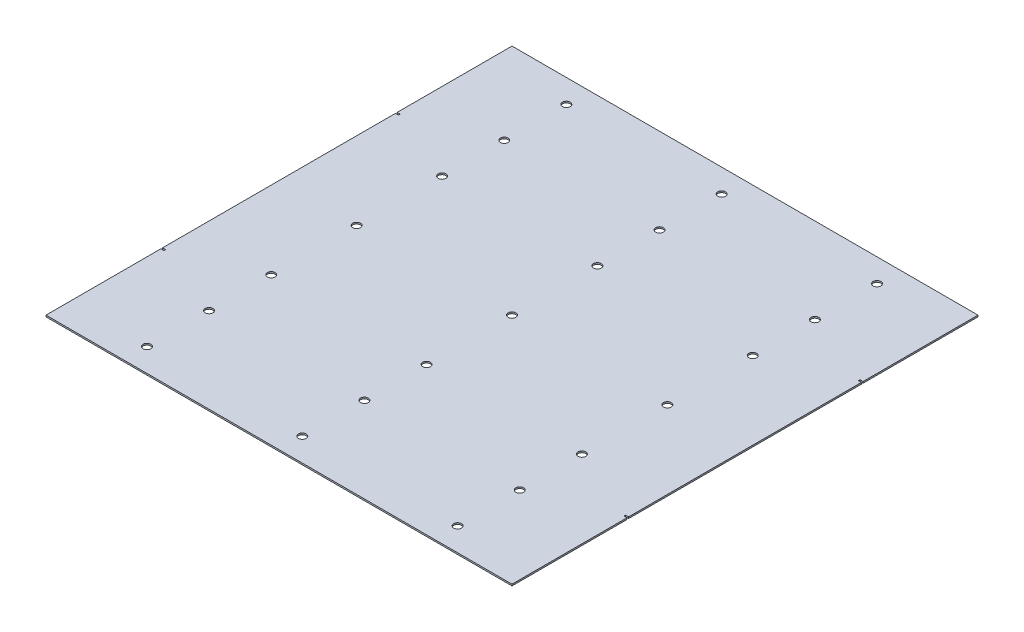
SolidWorks part; units mm, degrees
ref_plane "Front Plane" through (0, 0, 0) normal (0, 0, 1) x (1, 0, 0)
ref_plane "Top Plane" through (0, 0, 0) normal (0, 1, 0) x (1, 0, 0)
ref_plane "Right Plane" through (0, 0, 0) normal (1, 0, 0) x (0, 0, -1)
sketch "Sketch1" plane through (0, 0, 0) normal (0, 1, 0) x (1, 0, 0)
  line L0 (0, 0) -> (0, 74)
  line L5 (0, 74) -> (2, 74)
  line L6 (2, 74) -> (2, 75)
  line L11 (2, 75) -> (0, 75)
  line L12 (0, 75) -> (0, 225)
  line L51 (0, 225) -> (2, 225)
  line L53 (2, 225) -> (2, 226)
  line L54 (2, 226) -> (0, 226)
  line L55 (0, 226) -> (0, 300)
  line L56 (0, 300) -> (300, 300)
  line L57 (300, 300) -> (300, 226)
  line L58 (300, 226) -> (298, 226)
  line L59 (298, 226) -> (298, 225)
  line L60 (298, 225) -> (300, 225)
  line L61 (300, 225) -> (300, 75)
  line L62 (300, 75) -> (298, 75)
  line L63 (298, 75) -> (298, 74)
  line L64 (298, 74) -> (300, 74)
  line L65 (300, 74) -> (300, 0)
  line L66 (300, 0) -> (0, 0)
  line L67 (2, 75) -> (298, 75) construction
  line L68 (2, 225) -> (298, 225) construction
  line L69 (2, 75) -> (2, 225) construction
  line L70 (298, 75) -> (298, 225) construction
  line L71 (300, 74) -> (300, 75) construction
  line L72 (300, 225) -> (300, 226) construction
  line L73 (0, 225) -> (0, 226) construction
  line L74 (0, 74) -> (0, 75) construction
  line L75 (2, 226) -> (298, 226) construction
  line L76 (298, 74) -> (2, 74) construction
  line L77 (50, 285) -> (50, 245) construction
  line L78 (50, 245) -> (50, 205) construction
  line L79 (50, 205) -> (50, 95) construction
  line L80 (50, 95) -> (50, 55) construction
  line L81 (50, 55) -> (50, 15) construction
  line L83 (0, 35) -> (50, 35) construction
  line L85 (0, 265) -> (50, 265) construction
  circle A27 centre (50, 285) radius 2.5
  circle A28 centre (50, 245) radius 2.5
  circle A29 centre (50, 205) radius 2.5
  circle A30 centre (50, 150) radius 2.5
  circle A31 centre (50, 95) radius 2.5
  circle A32 centre (50, 55) radius 2.5
  circle A33 centre (50, 15) radius 2.5
  circle A34 centre (150, 15) radius 2.5
  circle A35 centre (150, 55) radius 2.5
  circle A36 centre (150, 95) radius 2.5
  circle A37 centre (150, 150) radius 2.5
  circle A38 centre (150, 205) radius 2.5
  circle A39 centre (150, 245) radius 2.5
  circle A40 centre (150, 285) radius 2.5
  circle A41 centre (250, 15) radius 2.5
  circle A42 centre (250, 55) radius 2.5
  circle A43 centre (250, 95) radius 2.5
  circle A44 centre (250, 150) radius 2.5
  circle A45 centre (250, 205) radius 2.5
  circle A46 centre (250, 245) radius 2.5
  circle A47 centre (250, 285) radius 2.5
  dimension "D5" = 2
  dimension "D6" = 40
  dimension "D11" = 20
  dimension "D9" = 40
  dimension "D13" = 5
  dimension "D1" = 150
  dimension "D2" = 75
  dimension "D3" = 75
  dimension "D4" = 1
  dimension "D7" = 40
  dimension "D8" = 40
  dimension "D10" = 20
  dimension "D12" = 50
  dimension "D14" = 100
  dimension "D15" = 50
  dimension "D16" = 55
extrude "Boss-Extrude1" add sketch "Sketch1" along normal blind 1
